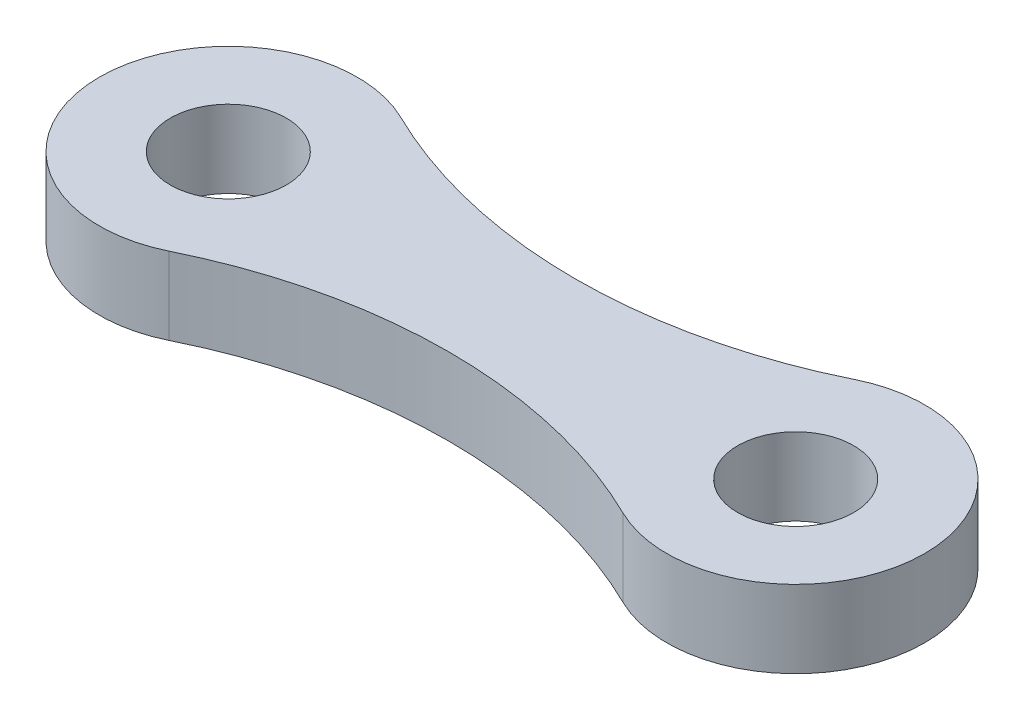
SolidWorks part; units mm, degrees
ref_plane "Ön Düzlem" through (0, 0, 0) normal (0, 0, 1) x (1, 0, 0)
ref_plane "Üst Düzlem" through (0, 0, 0) normal (0, 1, 0) x (1, 0, 0)
ref_plane "Sağ Düzlem" through (0, 0, 0) normal (1, 0, 0) x (0, 0, -1)
sketch "Çizim1" plane through (0, 0, 0) normal (0, 1, 0) x (1, 0, 0)
  line L1 (-4.375, 0) -> (1.625, 0) construction
  arc A0 (-4.4, 2.245) -> (-4.4, -2.245) centre (-5.5, 0) ccw
  arc A1 (4.4, -2.245) -> (4.4, 2.245) centre (5.5, 0) ccw
  circle A3 centre (-5.5, 0) radius 1.125
  circle A4 centre (5.5, 0) radius 1.125
  arc A5 (-4.4, 2.245) -> (4.4, 2.245) centre (0, 11.225) ccw
  arc A6 (-4.4, -2.245) -> (4.4, -2.245) centre (0, -11.225) cw
  point P1 (-4.375, 0)
  point P14 (4.7783, 3.1624)
  point P15 (-4.7576, 2.3872)
  point P16 (5.4274, 2.3303)
  point P17 (0, 1.225)
  dimension "D1" = 5
  dimension "D2" = 2.25
  dimension "D4" = 10
  dimension "D5" = 5.5
  dimension "D3" = 6
extrude "Yükseklik-Ekstrüzyon1" add sketch "Çizim1" along normal blind 1.5
